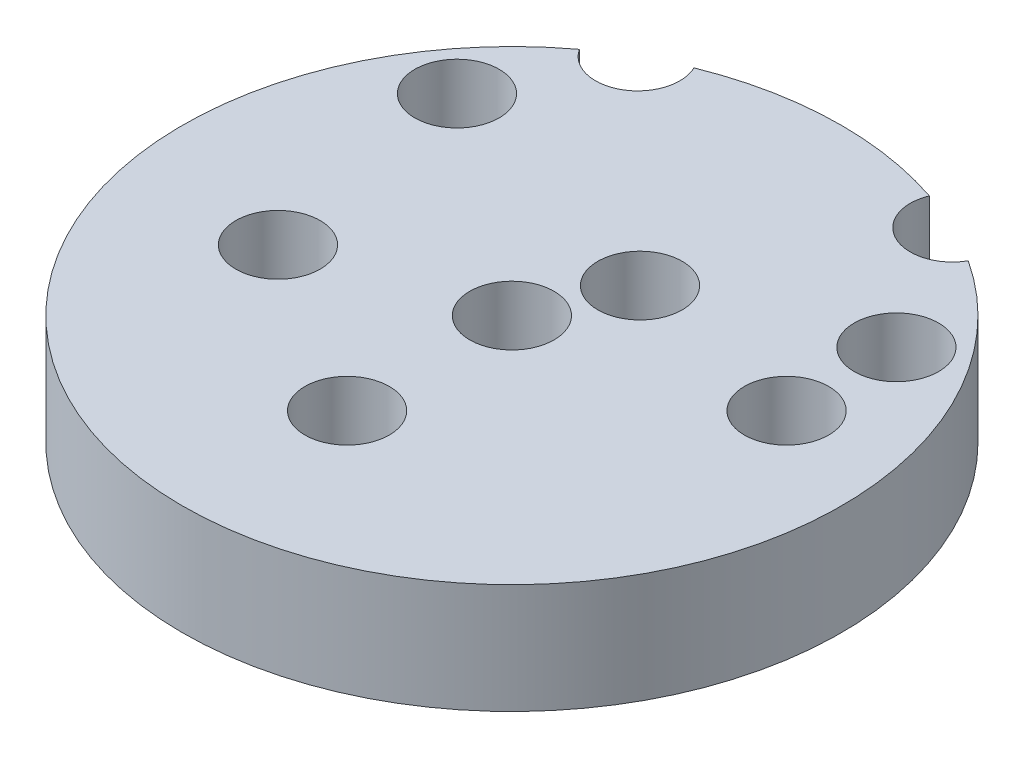
SolidWorks part; units mm, degrees
ref_plane "Front Plane" through (0, 0, 0) normal (0, 0, 1) x (1, 0, 0)
ref_plane "Top Plane" through (0, 0, 0) normal (0, 1, 0) x (1, 0, 0)
ref_plane "Right Plane" through (0, 0, 0) normal (1, 0, 0) x (0, 0, -1)
sketch "Sketch1" plane through (0, 0, 0) normal (0, 1, 0) x (1, 0, 0)
  circle A0 centre (0, 0) radius 76.2
  dimension "D1" = 152.4
extrude "Boss-Extrude1" add sketch "Sketch1" against normal blind 25.4
sketch "Sketch2" plane through (0, 0, 0) normal (0, 1, 0) x (1, 0, 0)
  line L1 (-50.8, -38.1) -> (50.8, -38.1)
  line L2 (-50.8, -38.1) -> (-50.8, 38.1)
  line L3 (-50.8, 38.1) -> (50.8, 38.1)
  line L4 (50.8, -38.1) -> (50.8, 38.1)
  line L5 (-50.8, -38.1) -> (50.8, 38.1) construction
  line L6 (-50.8, 38.1) -> (50.8, -38.1) construction
  point P0 (0, 0)
  dimension "D1" = 76.2
  dimension "D2" = 101.6
hole_wizard "M22x2.5 Tapped Hole1" positions "Sketch3" profile "Sketch4" tap size "M22x2.5" standard "ANSI Metric" end condition through all
sketch "Sketch3" plane through (0, 0, 0) normal (0, 1, 0) x (1, 0, 0)
  line L1 (-50.8, -38.1) -> (50.8, -38.1) construction
  line L2 (-37.3373, 66.4256) -> (33.3069, 68.5353) construction
  line L3 (33.3069, 68.5353) -> (8.7998, 20.819) construction
  line L4 (8.7998, 20.819) -> (-41.2086, -12.8777) construction
  circle A0 centre (0, 0) radius 76.2 construction
  point P2 (50.8, 12.7)
  point P4 (0, -38.1)
  point P6 (0, 0)
  point P10 (-50.8, 38.1)
  point P16 (50.8, 38.1)
  point P36 (-37.3373, 66.4256)
  point P37 (33.3069, 68.5353)
  point P39 (8.7998, 20.819)
  point P42 (-41.2086, -12.8777)
  point P53 (33.3069, 68.5353)
  point P56 (-37.3373, 66.4256)
  dimension "D1" = 50.8
  dimension "D2" = 12.7
sketch "Sketch4" plane through (50.8, 0, -12.7) normal (1, 0, 0) x (0, 0, 1)
  line L0 (0, 0) -> (0, 25.4)
  line L1 (0, 25.4) -> (9.75, 25.4)
  line L2 (9.75, 25.4) -> (9.75, 0)
  line L5 (9.75, 0) -> (0, 0)
  line L11 (0, -6.35) -> (0, 107.95) construction
  dimension "Thread Major Dia." = 19.5
  dimension "Thru Tap Drill Depth" = 25.4
